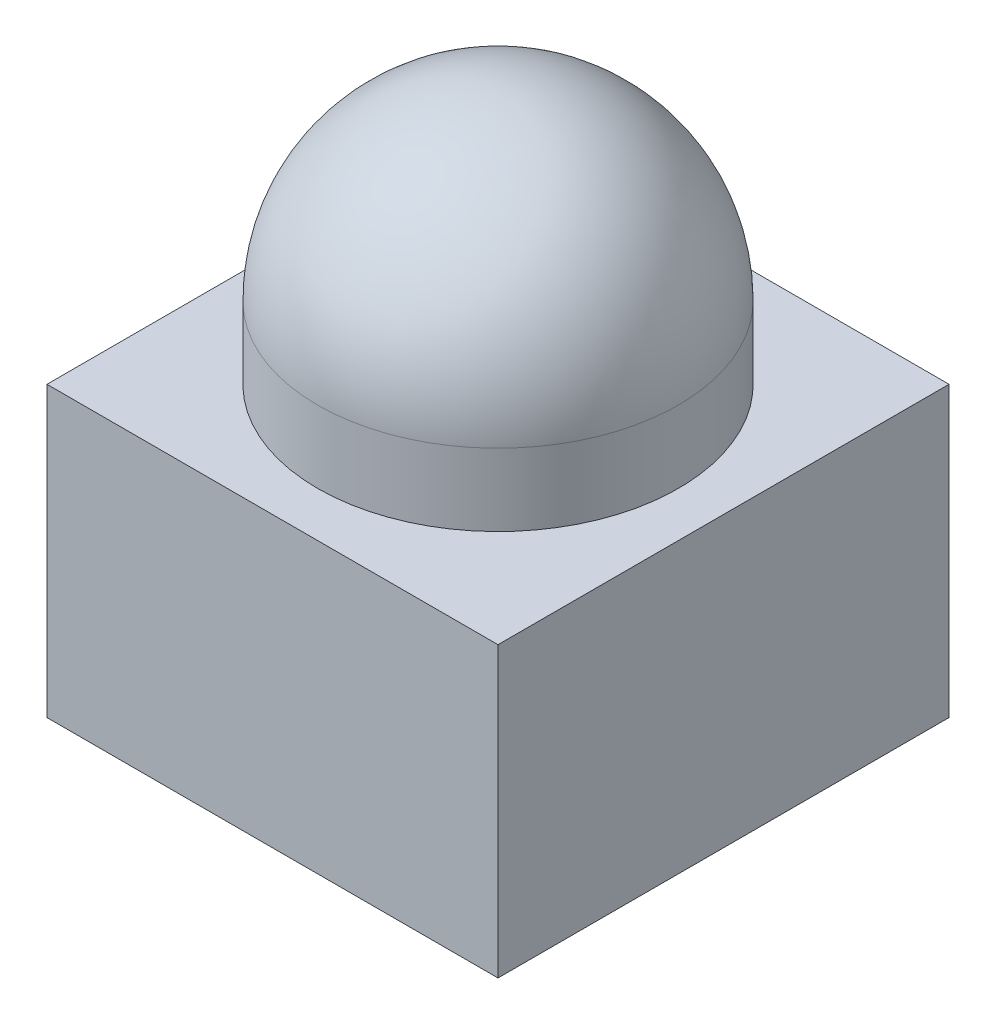
SolidWorks part; units mm, degrees
ref_plane "Front Plane" through (0, 0, 0) normal (0, 0, 1) x (1, 0, 0)
ref_plane "Top Plane" through (0, 0, 0) normal (0, 1, 0) x (1, 0, 0)
ref_plane "Right Plane" through (0, 0, 0) normal (1, 0, 0) x (0, 0, -1)
sketch "Sketch1" plane through (0, 0, 0) normal (0, 1, 0) x (1, 0, 0)
  line L1 (0, 0) -> (2.5, 0)
  line L2 (0, 0) -> (0, 2.5)
  line L3 (0, 2.5) -> (2.5, 2.5)
  line L4 (2.5, 0) -> (2.5, 2.5)
  dimension "D1" = 2.5
  dimension "D2" = 2.5
extrude "Boss-Extrude1" add sketch "Sketch1" along normal blind 1.6
sketch "Sketch2" plane through (0, 1.6, 0) normal (0, 1, 0) x (1, 0, 0)
  circle A0 centre (1.25, 1.25) radius 1
  dimension "D1" = 2
extrude "Boss-Extrude2" add sketch "Sketch2" along normal blind 1.4
fillet "Fillet1" radius 1 1 edges at (1.25, 3, -0.25)
